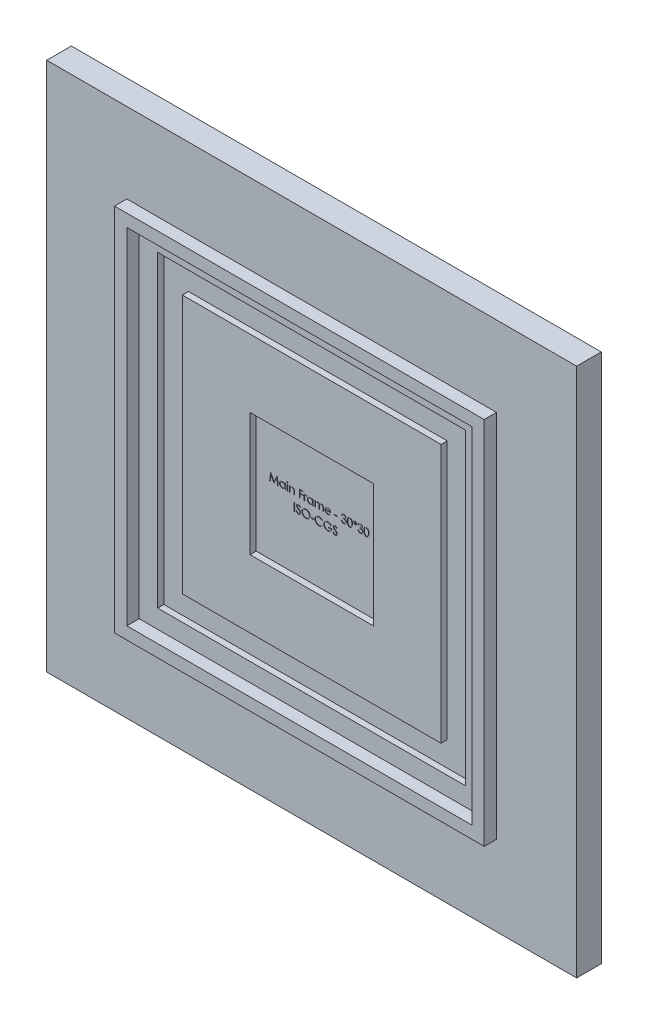
SolidWorks part; units mm, degrees
ref_plane "정면" through (0, 0, 0) normal (0, 0, 1) x (1, 0, 0)
ref_plane "윗면" through (0, 0, 0) normal (0, 1, 0) x (1, 0, 0)
ref_plane "우측면" through (0, 0, 0) normal (1, 0, 0) x (0, 0, -1)
sketch "스케치2" plane through (0, 0, 0) normal (0, 0, 1) x (1, 0, 0)
  line L1 (-215, 215) -> (215, 215)
  line L2 (-215, 215) -> (-215, -215)
  line L3 (-215, -215) -> (215, -215)
  line L4 (215, 215) -> (215, -215)
  line L5 (-215, 215) -> (215, -215) construction
  line L6 (-215, -215) -> (215, 215) construction
  point P0 (0, 0)
  dimension "D1" = 430
  dimension "D2" = 430
extrude "보스-돌출1" add sketch "스케치2" along normal blind 20
sketch "스케치3" plane through (0, 0, 20) normal (0, 0, 1) x (1, 0, 0)
  line L1 (-140, 140) -> (140, 140)
  line L2 (-140, 140) -> (-140, -140)
  line L3 (-140, -140) -> (140, -140)
  line L4 (140, 140) -> (140, -140)
  line L5 (-140, 140) -> (140, -140) construction
  line L6 (-140, -140) -> (140, 140) construction
  line L7 (-150, 150) -> (150, 150)
  line L8 (-150, 150) -> (-150, -150)
  line L9 (-150, -150) -> (150, -150)
  line L10 (150, 150) -> (150, -150)
  line L11 (-150, 150) -> (150, -150) construction
  line L12 (-150, -150) -> (150, 150) construction
  point P0 (0, 0)
  point P6 (0, 0)
  dimension "D1" = 280
  dimension "D2" = 280
extrude "보스-돌출2" add sketch "스케치3" along normal blind 10
sketch "스케치6" plane through (0, 0, 20) normal (0, 0, 1) x (1, 0, 0)
  line L1 (-50, 50) -> (50, 50)
  line L2 (-50, 50) -> (-50, -50)
  line L3 (-50, -50) -> (50, -50)
  line L4 (50, 50) -> (50, -50)
  line L5 (-50, 50) -> (50, -50) construction
  line L6 (-50, -50) -> (50, 50) construction
  line L7 (-105, 105) -> (105, 105)
  line L8 (-105, 105) -> (-105, -105)
  line L9 (-105, -105) -> (105, -105)
  line L10 (105, 105) -> (105, -105)
  line L11 (-105, 105) -> (105, -105) construction
  line L12 (-105, -105) -> (105, 105) construction
  line L13 (-125, 125) -> (125, 125)
  line L14 (-125, 125) -> (-125, -125)
  line L15 (-125, -125) -> (125, -125)
  line L16 (125, 125) -> (125, -125)
  line L17 (-125, 125) -> (125, -125) construction
  line L18 (-125, -125) -> (125, 125) construction
  point P0 (0, 0)
  point P6 (0, 0)
  point P11 (0, 0)
  dimension "D1" = 100
  dimension "D2" = 250
  dimension "10" = 100
  dimension "D3" = 250
  dimension "D4" = 20
  dimension "D5" = 20
extrude "컷-돌출2" cut sketch "스케치6" against normal blind 5 contours L16 L13 L14 L15 L7 L10 L9 L8 | L4 L1 L2 L3
sketch "스케치7" plane through (0, 0, 15) normal (0, 0, 1) x (1, 0, 0)
  text T0 "Main Frame - 30*30\r\n        ISO-CGS" font "Century Gothic" height in points 24
extrude "컷-돌출3" cut sketch "스케치7" against normal blind 0.4
